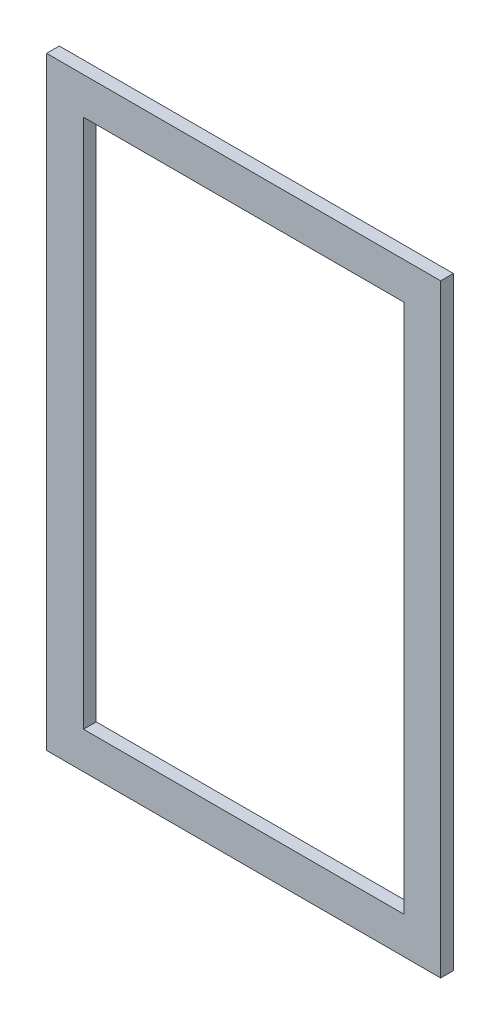
SolidWorks part; units mm, degrees
ref_plane "Plano frontal" through (0, 0, 0) normal (0, 0, 1) x (1, 0, 0)
ref_plane "Plano superior" through (0, 0, 0) normal (0, 1, 0) x (1, 0, 0)
ref_plane "Plano direito" through (0, 0, 0) normal (1, 0, 0) x (0, 0, -1)
sketch "Esboço1" plane through (0, 0, 0) normal (0, 0, 1) x (1, 0, 0)
  line L0 (15.5, 44.6) -> (15.5, 2.9) construction
  line L1 (0, 0) -> (31, 0)
  line L2 (0, 0) -> (0, 47.5)
  line L3 (0, 47.5) -> (31, 47.5)
  line L4 (31, 0) -> (31, 47.5)
  line L5 (2.9, 2.9) -> (28.1, 2.9)
  line L6 (2.9, 2.9) -> (2.9, 44.6)
  line L7 (2.9, 44.6) -> (28.1, 44.6)
  line L8 (28.1, 2.9) -> (28.1, 44.6)
  line L9 (2.9, 23.75) -> (28.1, 23.75) construction
  point P13 (0, 23.75)
  point P14 (15.5, 47.5)
  dimension "D1" = 25.2
  dimension "D2" = 41.7
  dimension "D3" = 31
  dimension "D4" = 47.5
extrude "Ressalto-extrusão1" add sketch "Esboço1" along normal blind 1
